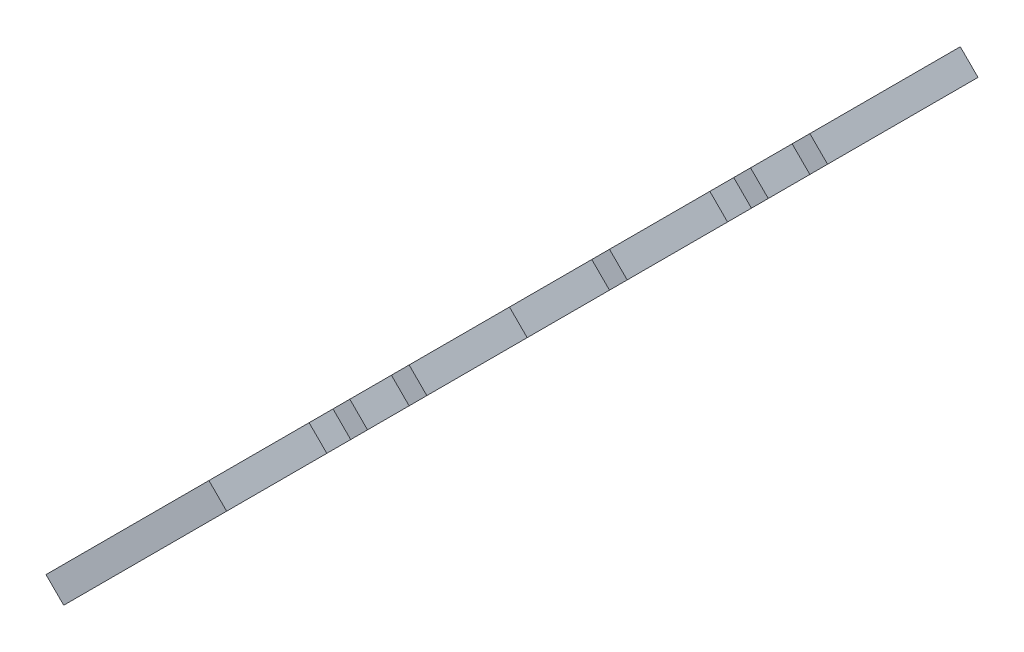
SolidWorks part; units mm, degrees
ref_plane "Front Plane" through (0, 0, 0) normal (0, 0, 1) x (1, 0, 0)
ref_plane "Top Plane" through (0, 0, 0) normal (0, 1, 0) x (1, 0, 0)
ref_plane "Right Plane" through (0, 0, 0) normal (1, 0, 0) x (0, 0, -1)
sketch "Sketch1" plane through (0, 0, 0) normal (0, 0, 1) x (1, 0, 0)
  line L0 (-108.2121, 4.5408) -> (-66.9029, 45.85)
  line L1 (-108.2121, 4.5408) -> (-112.7022, 9.0309)
  line L2 (-66.9029, 45.85) -> (-71.393, 50.3401)
  line L3 (-112.7022, 9.0309) -> (-71.393, 50.3401)
  line L4 (-76.7812, -26.8901) -> (-72.2911, -22.4) construction
extrude "Boss-Extrude1" add sketch "Sketch1" along normal up to surface (190.5 mm away)
sketch "Sketch2" plane through (-60.8666, 60.8666, 0) normal (-0.7071, 0.7071, 0) x (0, 0, 1)
  line L0 (190.5, -14.8867) -> (0, -14.8867) construction
  line L1 (165.1, -21.2367) -> (139.7412, -21.2367)
  line L2 (165.1, -21.2367) -> (165.1, -14.8867)
  line L3 (165.1, -14.8867) -> (139.7412, -14.8867)
  line L4 (139.7412, -21.2367) -> (139.7412, -14.8867)
  line L5 (190.5, -73.3067) -> (0, -73.3067) construction
  line L6 (165.1, -66.9567) -> (139.7412, -66.9567)
  line L7 (165.1, -66.9567) -> (165.1, -73.3067)
  line L8 (165.1, -73.3067) -> (139.7412, -73.3067)
  line L9 (139.7412, -66.9567) -> (139.7412, -73.3067)
  dimension "D1" = 25.3588
extrude "Cut-Extrude1" cut sketch "Sketch2" against normal blind 6.35
pattern_linear "LPattern1" count 3 spacing 50.8 along (0, 0, -1) of "Cut-Extrude1"
sketch "Sketch3" plane through (0, 0, 0) normal (0, 0, -1) x (-1, 0, 0)
  line L0 (92.4966, 20.2562) -> (96.9868, 24.7464)
  line L1 (108.2121, 4.5408) -> (66.9029, 45.85) construction
  line L2 (71.393, 50.3401) -> (112.7022, 9.0309) construction
  line L3 (96.9868, 24.7464) -> (88.0065, 33.7266)
  line L4 (88.0065, 33.7266) -> (83.4195, 29.3333)
  line L5 (187.6134, 29.3333) -> (16.1634, 29.3333) construction
  line L6 (83.4195, 29.3333) -> (92.4966, 20.2562)
  dimension "D1" = 12.7
  dimension "D2" = 6.35
  dimension "D3" = 22.225
extrude "Boss-Extrude2" add sketch "Sketch3" along normal blind 6.35
sketch "Sketch5" plane through (-56.3764, 56.3764, 0) normal (0.7071, -0.7071, 0) x (0, 0, -1)
  line L0 (-179.9336, -73.3067) -> (-175.6664, -66.9567) construction
  line L1 (-190.5, -73.3067) -> (-165.1, -73.3067) construction
  line L2 (-179.9336, -66.9567) -> (-179.9336, -73.3067) construction
  line L3 (-175.6664, -73.3067) -> (-179.9336, -66.9567) construction
  line L4 (-175.6664, -66.9567) -> (-175.6664, -73.3067) construction
  line L5 (-78.3336, -73.3067) -> (-74.0664, -66.9567) construction
  line L6 (-88.9412, -73.3067) -> (-63.5, -73.3067) construction
  line L7 (-78.3336, -66.9567) -> (-78.3336, -73.3067) construction
  line L8 (-74.0664, -73.3067) -> (-78.3336, -66.9567) construction
  line L9 (-74.0664, -66.9567) -> (-74.0664, -73.3067) construction
  line L10 (-18.0086, -73.3067) -> (-13.7414, -66.9567) construction
  line L11 (-38.1412, -73.3067) -> (0, -73.3067) construction
  line L12 (-18.0086, -66.9567) -> (-18.0086, -73.3067) construction
  line L13 (-13.7414, -73.3067) -> (-18.0086, -66.9567) construction
  line L14 (-13.7414, -66.9567) -> (-13.7414, -73.3067) construction
  circle A0 centre (-177.8, -70.1317) radius 2.0955
  circle A1 centre (-76.2, -70.1317) radius 2.0955
  circle A2 centre (-15.875, -70.1317) radius 2.0955
  dimension "D1" = 4.191
extrude "Cut-Extrude2" cut sketch "Sketch5" against normal through all
ref_plane "Midplane" through (-31.1811, -31.1811, 0) normal (-0.7071, -0.7071, 0) x (-0.7071, 0.7071, 0)
mirror "Mirror1" about plane through (-31.1811, -31.1811, 0) normal (-0.7071, -0.7071, 0) of "Cut-Extrude2"
sketch "Sketch6" plane through (-60.8666, 60.8666, 0) normal (-0.7071, 0.7071, 0) x (0, 0, 1)
  line L0 (152.4206, -3.6091) -> (152.4206, -40.9822) construction
  line L1 (139.7412, -14.8867) -> (139.7412, -21.2367) construction
  line L2 (165.1, -21.2367) -> (165.1, -14.8867) construction
  line L3 (50.8206, 6.6062) -> (50.8206, -35.0025) construction
  line L4 (38.1412, -14.8867) -> (38.1412, -21.2367) construction
  line L5 (63.5, -21.2367) -> (63.5, -14.8867) construction
  line L7 (38.1412, -21.2367) -> (63.5, -21.2367) construction
  line L11 (139.7412, -21.2367) -> (165.1, -21.2367) construction
  line B0 (52.9542, -21.2367) -> (48.687, -21.2367)
  line B1 (48.687, -33.1747) -> (46.3756, -33.1747)
  line B2 (46.3756, -33.1747) -> (46.3756, -29.9997)
  line B3 (46.3756, -29.9997) -> (48.687, -29.9997)
  line B4 (48.687, -29.9997) -> (48.687, -21.2367)
  line B5 (48.687, -33.1747) -> (48.687, -36.4767)
  line B6 (48.687, -36.4767) -> (52.9542, -36.4767)
  line B7 (52.9542, -33.1747) -> (52.9542, -36.4767)
  line B8 (52.9542, -29.9997) -> (52.9542, -21.2367)
  line B9 (55.2656, -29.9997) -> (52.9542, -29.9997)
  line B10 (55.2656, -33.1747) -> (55.2656, -29.9997)
  line B11 (52.9542, -33.1747) -> (55.2656, -33.1747)
  line B12 (154.5542, -21.2367) -> (150.287, -21.2367)
  line B13 (150.287, -33.1747) -> (147.9756, -33.1747)
  line B14 (147.9756, -33.1747) -> (147.9756, -29.9997)
  line B15 (147.9756, -29.9997) -> (150.287, -29.9997)
  line B16 (150.287, -29.9997) -> (150.287, -21.2367)
  line B17 (150.287, -33.1747) -> (150.287, -36.4767)
  line B18 (150.287, -36.4767) -> (154.5542, -36.4767)
  line B19 (154.5542, -33.1747) -> (154.5542, -36.4767)
  line B20 (154.5542, -29.9997) -> (154.5542, -21.2367)
  line B21 (156.8656, -29.9997) -> (154.5542, -29.9997)
  line B22 (156.8656, -33.1747) -> (156.8656, -29.9997)
  line B23 (154.5542, -33.1747) -> (156.8656, -33.1747)
sketch_block_instance "TSlot-1"
sketch_block "TSlot" parameters "D1"=3.302, "D2"=3.175
sketch_block_instance "TSlot-2"
extrude "Cut-Extrude3" cut sketch "Sketch6" against normal through all
mirror "Mirror2" about plane through (-31.1811, -31.1811, 0) normal (-0.7071, -0.7071, 0) of "Cut-Extrude3"
